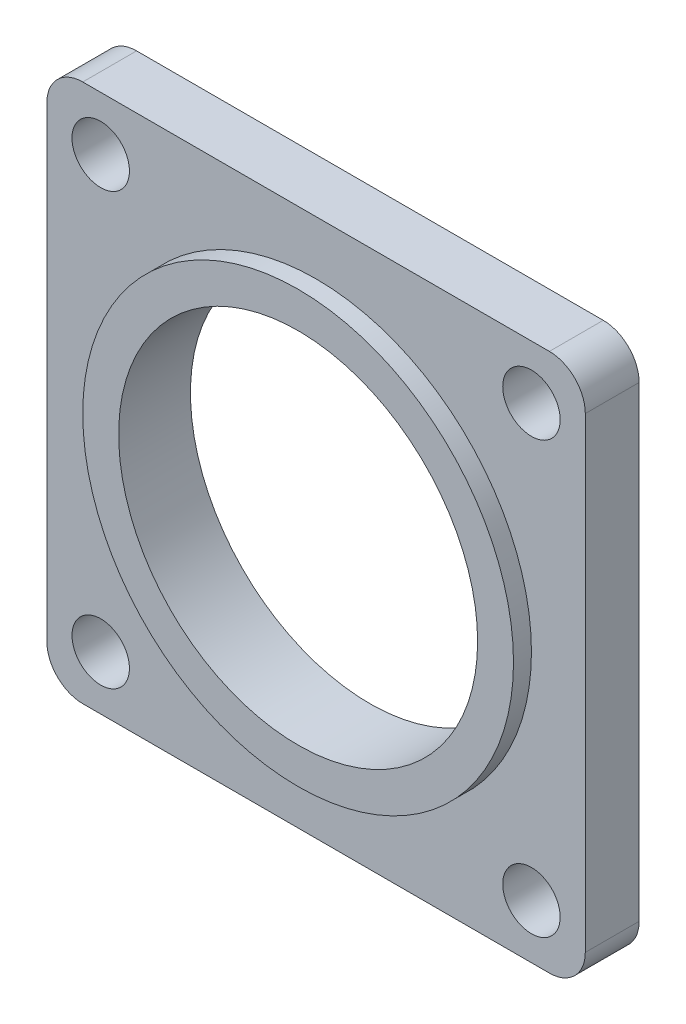
SolidWorks part; units mm, degrees
material "6061 合金"
ref_plane "前视基准面" through (0, 0, 0) normal (0, 0, 1) x (1, 0, 0)
ref_plane "上视基准面" through (0, 0, 0) normal (0, 1, 0) x (1, 0, 0)
ref_plane "右视基准面" through (0, 0, 0) normal (1, 0, 0) x (0, 0, -1)
sketch "草图1" plane through (0, 0, 0) normal (0, 0, 1) x (1, 0, 0)
  line L1 (-15, 15) -> (15, 15)
  line L2 (-15, 15) -> (-15, -15)
  line L3 (-15, -15) -> (15, -15)
  line L4 (15, 15) -> (15, -15)
  line L5 (0, -15) -> (0, 15) construction
  line L6 (-15, 0) -> (15, 0) construction
  point P56 (0, 0)
  dimension "D1" = 30
  dimension "D2" = 30
extrude "凸台-拉伸1" add sketch "草图1" along normal blind 3
sketch "草图2" plane through (0, 0, 3) normal (0, 0, 1) x (1, 0, 0)
  circle A0 centre (0, 0) radius 12
  circle A1 centre (0, 0) radius 10
  dimension "D1" = 24
  dimension "D2" = 2
extrude "凸台-拉伸2" add sketch "草图2" along normal blind 1 contours A0 A1
sketch "草图3" plane through (0, 0, 4) normal (0, 0, 1) x (1, 0, 0)
  circle A1 centre (0, 0) radius 10
  circle A2 centre (0, 0) radius 10
  circle A3 centre (0, 0) radius 12
  circle A4 centre (0, 0) radius 12 construction
  dimension "D1" = 0
  dimension "D2" = 0
extrude "切除-拉伸2" cut sketch "草图3" against normal through all contours A2 | A4
sketch "草图4" plane through (0, 0, 0) normal (0, 0, -1) x (-1, 0, 0)
  line L1 (-12, 12) -> (12, 12) construction
  line L2 (-12, 12) -> (-12, -12) construction
  line L3 (-12, -12) -> (12, -12) construction
  line L4 (12, 12) -> (12, -12) construction
  line L5 (0, -12) -> (0, 12) construction
  line L6 (-12, 0) -> (12, 0) construction
  circle A0 centre (12, 12) radius 1.6
  circle A1 centre (-12, 12) radius 1.6
  circle A2 centre (12, -12) radius 1.6
  circle A3 centre (-12, -12) radius 1.6
  point P92 (0, 0)
  dimension "D3" = 3.2
  dimension "D1" = 24
  dimension "D2" = 24
extrude "切除-拉伸3" cut sketch "草图4" against normal through all
fillet "圆角1" radius 2 4 edges at (15, -15, 1.5) (-15, -15, 1.5) (-15, 15, 1.5) (15, 15, 1.5)
